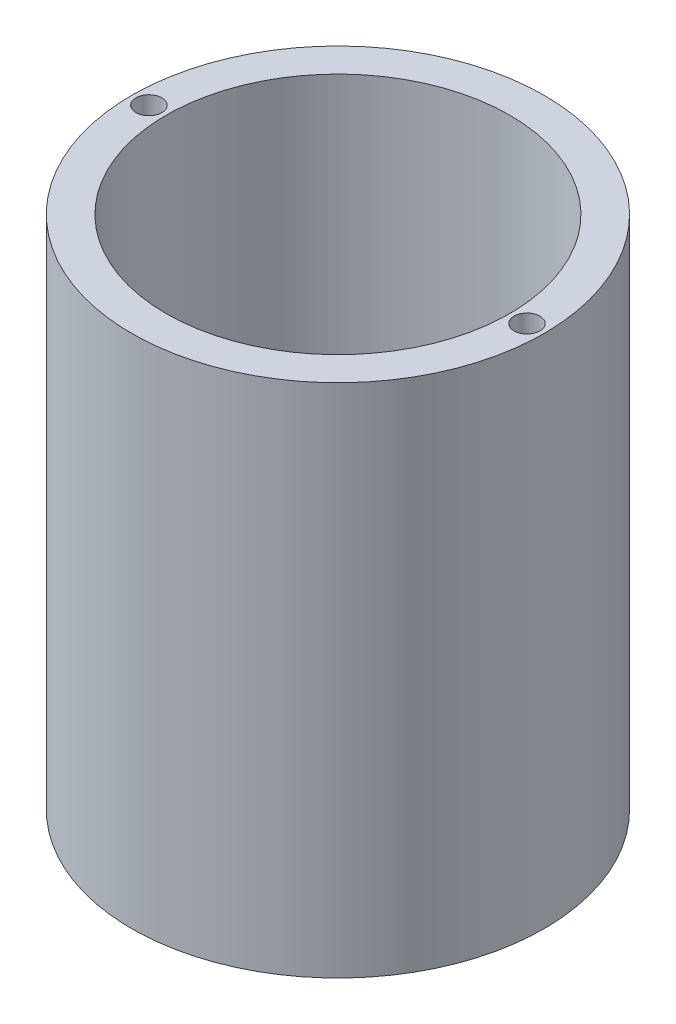
SolidWorks part; units mm, degrees
material "Chrome Stainless Steel"
ref_plane "Front Plane" through (0, 0, 0) normal (0, 0, 1) x (1, 0, 0)
ref_plane "Top Plane" through (0, 0, 0) normal (0, 1, 0) x (1, 0, 0)
ref_plane "Right Plane" through (0, 0, 0) normal (1, 0, 0) x (0, 0, -1)
sketch "Sketch1" plane through (0, 0, 0) normal (0, 1, 0) x (1, 0, 0)
  circle A0 centre (0, 0) radius 12.7
  circle A1 centre (0, 0) radius 15.24
  dimension "D1" = 2.54
  dimension "D2" = 25.4
extrude "Boss-Extrude1" add sketch "Sketch1" along normal blind 38.1
sketch "Sketch2" plane through (0, 38.1, 0) normal (0, 1, 0) x (1, 0, 0)
  line L0 (-13.97, 0) -> (13.97, 0) construction
  circle A1 centre (-13.97, 0) radius 0.9525
  circle A2 centre (13.97, 0) radius 0.9525
  dimension "D1" = 1.905
  dimension "D2" = 27.94
extrude "Cut-Extrude1" cut sketch "Sketch2" against normal blind 5.08
